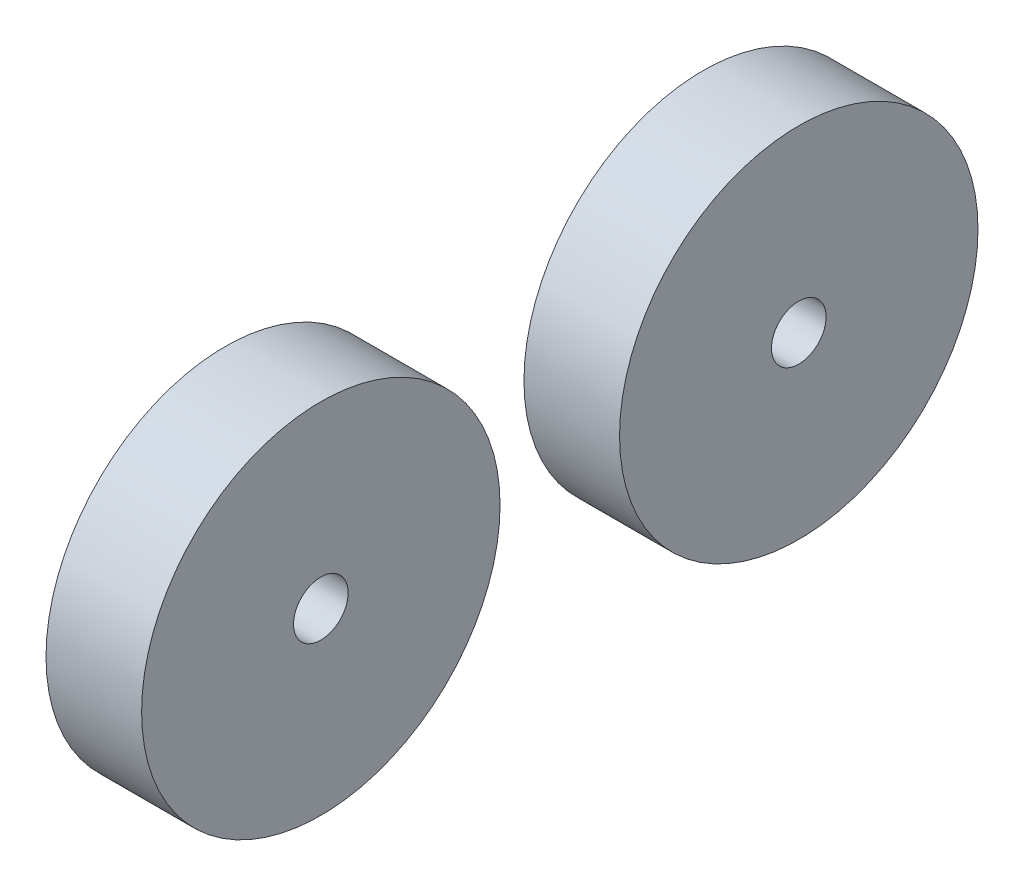
SolidWorks part; units mm, degrees
ref_plane "Front Plane" through (0, 0, 0) normal (0, 0, 1) x (1, 0, 0)
ref_plane "Top Plane" through (0, 0, 0) normal (0, 1, 0) x (1, 0, 0)
ref_plane "Right Plane" through (0, 0, 0) normal (1, 0, 0) x (0, 0, -1)
sketch "Sketch1" plane through (0, 0, 0) normal (1, 0, 0) x (0, 0, -1)
  line L0 (-20, 0) -> (20, 0) construction
  circle A1 centre (-20, 0) radius 15
  circle A2 centre (20, 0) radius 15
  circle A3 centre (20, 0) radius 2.286
  circle A4 centre (0, 0) radius 2.286
  circle A5 centre (-20, 0) radius 2.286
  point P6 (0, 0)
  point P17 (-15.7427, 10.0873)
  point P19 (-9.2505, 9.0053)
  point P20 (-41.9433, -12.8)
  point P21 (-25.3901, 19.2)
  point P22 (-10.8736, 12.8)
  point P23 (0, 0)
  point P24 (-18, 9.4216)
  point P25 (-18, 9.4216)
  point P26 (-18, 10.5082)
  point P27 (-12.3448, 10.8554)
  point P28 (-20.3292, 19.2)
  point P29 (-11.4093, 8.6212)
  point P30 (-13.9648, 19.2)
  point P31 (-12.692, 11.2215)
  point P32 (-16.6841, 11.2215)
  dimension "D2" = 30
  dimension "D4" = 40
  dimension "D5" = 4.572
extrude "Boss-Extrude2" add sketch "Sketch1" along normal blind 8
